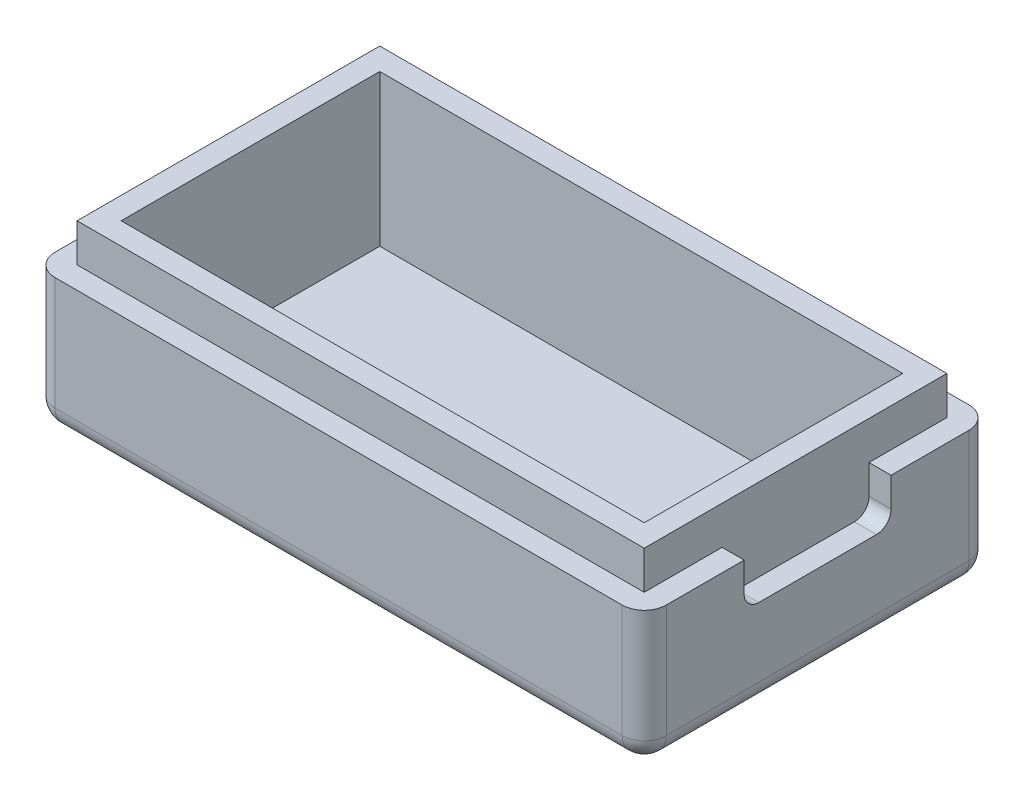
SolidWorks part; units mm, degrees
ref_plane "Front Plane" through (0, 0, 0) normal (0, 0, 1) x (1, 0, 0)
ref_plane "Top Plane" through (0, 0, 0) normal (0, 1, 0) x (1, 0, 0)
ref_plane "Right Plane" through (0, 0, 0) normal (1, 0, 0) x (0, 0, -1)
sketch "Sketch1" plane through (0, 0, 0) normal (0, 1, 0) x (1, 0, 0)
  line L1 (0, 0) -> (41.6, 0)
  line L2 (0, 0) -> (0, 23.6)
  line L3 (0, 23.6) -> (41.6, 23.6)
  line L4 (41.6, 0) -> (41.6, 23.6)
  dimension "D1" = 41.6
  dimension "D2" = 23.6
extrude "Boss-Extrude1" add sketch "Sketch1" along normal blind 11.8
sketch "Sketch2" plane through (0, 11.8, 0) normal (0, 1, 0) x (1, 0, 0)
  line L0 (20.8, 23.6) -> (20.8, 0) construction
  line L1 (41.6, 23.6) -> (0, 23.6) construction
  line L2 (0, 0) -> (41.6, 0) construction
  line L4 (3, 3) -> (38.6, 3)
  line L5 (3, 3) -> (3, 20.6)
  line L6 (3, 20.6) -> (38.6, 20.6)
  line L7 (38.6, 3) -> (38.6, 20.6)
  line L8 (3, 3) -> (38.6, 20.6) construction
  line L9 (3, 20.6) -> (38.6, 3) construction
  point P6 (20.8, 11.8)
  dimension "D1" = 17.6
  dimension "D2" = 35.6
extrude "Cut-Extrude1" cut sketch "Sketch2" against normal blind 10.3
sketch "Sketch4" plane through (0, 11.8, 0) normal (0, 1, 0) x (1, 0, 0)
  line L1 (0, 23.6) -> (41.6, 23.6)
  line L2 (0, 23.6) -> (0, 0)
  line L3 (0, 0) -> (41.6, 0)
  line L4 (41.6, 23.6) -> (41.6, 0)
  line L5 (1.5, 22.1) -> (40.1, 22.1)
  line L6 (1.5, 22.1) -> (1.5, 1.5)
  line L7 (1.5, 1.5) -> (40.1, 1.5)
  line L8 (40.1, 22.1) -> (40.1, 1.5)
  dimension "D1" = 1.5
  dimension "D2" = 1.5
  dimension "D3" = 1.5
  dimension "D4" = 1.5
extrude "Cut-Extrude2" cut sketch "Sketch4" against normal blind 2.6
fillet "Fillet1" radius 1.5 8 edges at (0, 4.6, 0) (0, 0, -11.8) (0, 4.6, -23.6) (41.6, 0, -11.8) (20.8, 0, -23.6) (20.8, 0, 0) (41.6, 4.6, -23.6) (41.6, 4.6, 0)
sketch "Sketch7" plane through (0, 0, 0) normal (-1, 0, 0) x (0, 0, 1)
  line L0 (-22.1, 9.2) -> (-1.5, 9.2) construction
  line L1 (-16.8, 9.2) -> (-6.8, 9.2)
  line L2 (-16.8, 9.2) -> (-16.8, 7.2)
  line L3 (-15.8, 6.2) -> (-7.8, 6.2)
  line L4 (-6.8, 9.2) -> (-6.8, 7.2)
  line L5 (-11.8, 6.2) -> (-11.8, 1.5) construction
  line L6 (-22.1, 1.5) -> (-1.5, 1.5) construction
  arc A0 (-7.8, 6.2) -> (-6.8, 7.2) centre (-7.8, 7.2) ccw
  arc A1 (-16.8, 7.2) -> (-15.8, 6.2) centre (-15.8, 7.2) ccw
  point P14 (-16.8, 6.2)
  dimension "D3" = 1
  dimension "D1" = 10
  dimension "D2" = 3
extrude "Cut-Extrude5" cut sketch "Sketch7" against normal up to surface (1.5 mm away) up to face at (1.5, 10.5, -11.8)
sketch "Sketch8" plane through (41.6, 0, 0) normal (1, 0, 0) x (0, 0, -1)
  line L1 (6.8, 9.2) -> (16.8, 9.2)
  line L2 (6.8, 9.2) -> (6.8, 7.2)
  line L3 (7.8, 6.2) -> (15.8, 6.2)
  line L4 (16.8, 9.2) -> (16.8, 7.2)
  arc A0 (15.8, 6.2) -> (16.8, 7.2) centre (15.8, 7.2) ccw
  arc A1 (6.8, 7.2) -> (7.8, 6.2) centre (7.8, 7.2) ccw
  point P8 (16.8, 6.2)
  dimension "D1" = 1
extrude "Cut-Extrude6" cut sketch "Sketch8" against normal up to surface (1.5 mm away) up to face at (40.1, 10.5, -11.8)
